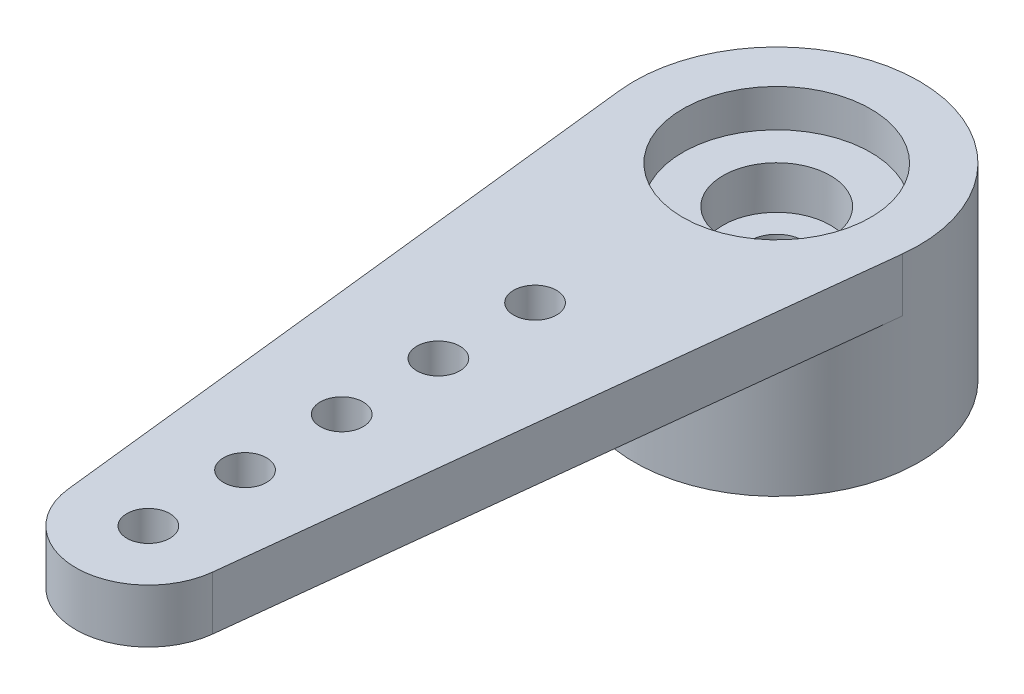
SolidWorks part; units mm, degrees
ref_plane "Front Plane" through (0, 0, 0) normal (0, 0, 1) x (1, 0, 0)
ref_plane "Top Plane" through (0, 0, 0) normal (0, 1, 0) x (1, 0, 0)
ref_plane "Right Plane" through (0, 0, 0) normal (1, 0, 0) x (0, 0, -1)
sketch "Sketch1" plane through (0, 0, 0) normal (0, 1, 0) x (1, 0, 0)
  line L0 (0, 0) -> (0, -14.859) construction
  line L1 (-1.7039, -15.0495) -> (-3.3447, -0.3739)
  line L2 (1.7039, -15.0495) -> (3.3447, -0.3739)
  arc A0 (3.3447, -0.3739) -> (-3.3447, -0.3739) centre (0, 0) ccw
  arc A1 (-1.7039, -15.0495) -> (1.7039, -15.0495) centre (0, -14.859) ccw
  dimension "D1" = 6.731
  dimension "D2" = 3.429
  dimension "D3" = 19.939
extrude "Boss-Extrude1" add sketch "Sketch1" along normal blind 1.27
sketch "Sketch2" plane through (0, 0, 0) normal (0, -1, 0) x (1, 0, 0)
  circle A0 centre (0, 0) radius 3.3655
extrude "Boss-Extrude2" add sketch "Sketch2" along normal blind 3.175
sketch "Sketch3" plane through (0, -3.175, 0) normal (0, -1, 0) x (-1, 0, 0)
  line L0 (0.3447, 2.4524) -> (0.1605, 2.2167)
  line L1 (0, 2.4765) -> (-0.1496, 2.2175)
  line L2 (0.4567, 2.1751) -> (0.3447, 2.4524)
  line L3 (0.1496, 2.2175) -> (0, 2.4765)
  line L4 (0.6826, 2.3806) -> (0.4675, 2.1728)
  line L5 (0.755, 2.0903) -> (0.6826, 2.3806)
  line L6 (1.0073, 2.2624) -> (0.7653, 2.0866)
  line L7 (1.0385, 1.9649) -> (1.0073, 2.2624)
  line L8 (1.3123, 2.1002) -> (1.0482, 1.9598)
  line L9 (1.3019, 1.8013) -> (1.3123, 2.1002)
  line L10 (1.5919, 1.8971) -> (1.3108, 1.7948)
  line L11 (1.5399, 1.6025) -> (1.5919, 1.8971)
  line L12 (1.8404, 1.6571) -> (1.5478, 1.5949)
  line L13 (1.748, 1.3726) -> (1.8404, 1.6571)
  line L14 (2.0531, 1.3848) -> (1.7547, 1.364)
  line L15 (1.922, 1.116) -> (2.0531, 1.3848)
  line L16 (2.2259, 1.0856) -> (1.9275, 1.1065)
  line L17 (2.0586, 0.8377) -> (2.2259, 1.0856)
  line L18 (2.3553, 0.7653) -> (2.0627, 0.8275)
  line L19 (2.1551, 0.543) -> (2.3553, 0.7653)
  line L20 (2.4389, 0.43) -> (2.1578, 0.5323)
  line L21 (2.2097, 0.2378) -> (2.4389, 0.43)
  line L22 (2.475, 0.0864) -> (2.2109, 0.2269)
  line L23 (2.2213, -0.0721) -> (2.475, 0.0864)
  line L24 (2.4629, -0.2589) -> (2.2209, -0.0831)
  line L25 (2.1897, -0.3805) -> (2.4629, -0.2589)
  line L26 (2.4029, -0.5991) -> (2.1878, -0.3913)
  line L27 (2.1154, -0.6816) -> (2.4029, -0.5991)
  line L28 (2.2962, -0.9277) -> (2.112, -0.692)
  line L29 (2, -0.9693) -> (2.2962, -0.9277)
  line L30 (2.1447, -1.2383) -> (1.9952, -0.9792)
  line L31 (1.8456, -1.2382) -> (2.1447, -1.2383)
  line L32 (1.9515, -1.5247) -> (1.8395, -1.2474)
  line L33 (1.6553, -1.4831) -> (1.9515, -1.5247)
  line L34 (1.7203, -1.7814) -> (1.648, -1.4912)
  line L35 (1.4328, -1.699) -> (1.7203, -1.7814)
  line L36 (1.4557, -2.0035) -> (1.4244, -1.7061)
  line L37 (1.1824, -1.8819) -> (1.4557, -2.0035)
  line L38 (1.1626, -2.1866) -> (1.1731, -1.8877)
  line L39 (0.909, -2.0281) -> (1.1626, -2.1866)
  line L40 (0.847, -2.3271) -> (0.899, -2.0326)
  line L41 (0.6179, -2.1349) -> (0.847, -2.3271)
  line L42 (0.5149, -2.4224) -> (0.6073, -2.1379)
  line L43 (0.3147, -2.2001) -> (0.5149, -2.4224)
  line L44 (0.1728, -2.4705) -> (0.3039, -2.2016)
  line L45 (-0.22, 2.0955) -> (0, 2.0955) [skipped]
  line L46 (0.0055, -2.2225) -> (0.1728, -2.4705)
  line L47 (-0.1728, -2.4705) -> (-0.0055, -2.2225)
  line L48 (-0.3039, -2.2016) -> (-0.1728, -2.4705)
  line L49 (-0.5149, -2.4224) -> (-0.3147, -2.2001)
  line L50 (-0.6073, -2.1379) -> (-0.5149, -2.4224)
  line L51 (-0.847, -2.3271) -> (-0.6179, -2.1349)
  line L52 (-0.899, -2.0326) -> (-0.847, -2.3271)
  line L53 (-1.1626, -2.1866) -> (-0.909, -2.0281)
  line L54 (-1.1731, -1.8877) -> (-1.1626, -2.1866)
  line L55 (-1.4557, -2.0035) -> (-1.1824, -1.8819)
  line L56 (-1.4244, -1.7061) -> (-1.4557, -2.0035)
  line L57 (-1.7203, -1.7814) -> (-1.4328, -1.699)
  line L58 (-1.648, -1.4912) -> (-1.7203, -1.7814)
  line L59 (-1.9515, -1.5247) -> (-1.6553, -1.4831)
  line L60 (-1.8395, -1.2474) -> (-1.9515, -1.5247)
  line L61 (-2.1447, -1.2382) -> (-1.8456, -1.2383)
  line L62 (-1.9952, -0.9792) -> (-2.1447, -1.2382)
  line L63 (-2.2962, -0.9277) -> (-2, -0.9693)
  line L64 (-2.112, -0.692) -> (-2.2962, -0.9277)
  line L65 (-2.4029, -0.5991) -> (-2.1154, -0.6816)
  line L66 (-2.1878, -0.3913) -> (-2.4029, -0.5991)
  line L67 (-2.4629, -0.2589) -> (-2.1897, -0.3805)
  line L68 (-2.2209, -0.0831) -> (-2.4629, -0.2589)
  line L69 (-2.475, 0.0864) -> (-2.2213, -0.0721)
  line L70 (-2.2109, 0.2269) -> (-2.475, 0.0864)
  line L71 (-2.4389, 0.43) -> (-2.2097, 0.2378)
  line L72 (-2.1578, 0.5323) -> (-2.4389, 0.43)
  line L73 (-2.3553, 0.7653) -> (-2.1551, 0.543)
  line L74 (-2.0627, 0.8275) -> (-2.3553, 0.7653)
  line L75 (-2.2259, 1.0856) -> (-2.0586, 0.8377)
  line L76 (-1.9275, 1.1065) -> (-2.2259, 1.0856)
  line L77 (-2.0531, 1.3848) -> (-1.922, 1.116)
  line L78 (-1.7547, 1.364) -> (-2.0531, 1.3848)
  line L79 (-1.8404, 1.6571) -> (-1.748, 1.3726)
  line L80 (-1.5478, 1.5949) -> (-1.8404, 1.6571)
  line L81 (-1.5919, 1.8971) -> (-1.5399, 1.6025)
  line L82 (-1.3108, 1.7948) -> (-1.5919, 1.8971)
  line L83 (-1.3123, 2.1002) -> (-1.3019, 1.8013)
  line L84 (-1.0482, 1.9598) -> (-1.3123, 2.1002)
  line L85 (-1.0073, 2.2624) -> (-1.0385, 1.9649)
  line L86 (-0.7653, 2.0866) -> (-1.0073, 2.2624)
  line L87 (-0.6826, 2.3806) -> (-0.755, 2.0903)
  line L88 (-0.4675, 2.1728) -> (-0.6826, 2.3806)
  line L89 (-0.3447, 2.4524) -> (-0.4567, 2.1751)
  line L90 (-0.1605, 2.2167) -> (-0.3447, 2.4524)
  arc A0 (-0.1496, 2.2175) -> (-0.1605, 2.2167) centre (0, 0) ccw
  circle A1 centre (0, 2.2225) radius 0.127 construction
  arc A2 (0.1605, 2.2167) -> (0.1496, 2.2175) centre (0, 0) ccw
  arc A3 (0.4675, 2.1728) -> (0.4567, 2.1751) centre (0, 0) ccw
  arc A4 (0.7653, 2.0866) -> (0.755, 2.0903) centre (0, 0) ccw
  arc A5 (1.0482, 1.9598) -> (1.0385, 1.9649) centre (0, 0) ccw
  arc A6 (1.3108, 1.7948) -> (1.3019, 1.8013) centre (0, 0) ccw
  arc A7 (1.5478, 1.5949) -> (1.5399, 1.6025) centre (0, 0) ccw
  arc A8 (1.7547, 1.364) -> (1.748, 1.3726) centre (0, 0) ccw
  arc A9 (1.9275, 1.1065) -> (1.922, 1.116) centre (0, 0) ccw
  arc A10 (-0.4567, 2.1751) -> (-0.4675, 2.1728) centre (0, 0) ccw
  arc A11 (-0.755, 2.0903) -> (-0.7653, 2.0866) centre (0, 0) ccw
  arc A12 (-1.0385, 1.9649) -> (-1.0482, 1.9598) centre (0, 0) ccw
  arc A13 (-1.3019, 1.8013) -> (-1.3108, 1.7948) centre (0, 0) ccw
  arc A14 (-1.5399, 1.6025) -> (-1.5478, 1.5949) centre (0, 0) ccw
  arc A15 (-1.748, 1.3726) -> (-1.7547, 1.364) centre (0, 0) ccw
  arc A16 (-1.922, 1.116) -> (-1.9275, 1.1065) centre (0, 0) ccw
  arc A17 (-2.0586, 0.8377) -> (-2.0627, 0.8275) centre (0, 0) ccw
  arc A18 (-2.1551, 0.543) -> (-2.1578, 0.5323) centre (0, 0) ccw
  arc A19 (-2.2097, 0.2378) -> (-2.2109, 0.2269) centre (0, 0) ccw
  arc A20 (-2.2213, -0.0721) -> (-2.2209, -0.0831) centre (0, 0) ccw
  arc A21 (2.0627, 0.8275) -> (2.0586, 0.8377) centre (0, 0) ccw
  arc A22 (2.1578, 0.5323) -> (2.1551, 0.543) centre (0, 0) ccw
  arc A23 (2.2109, 0.2269) -> (2.2097, 0.2378) centre (0, 0) ccw
  arc A24 (2.2209, -0.0831) -> (2.2213, -0.0721) centre (0, 0) ccw
  arc A25 (2.1878, -0.3913) -> (2.1897, -0.3805) centre (0, 0) ccw
  arc A26 (2.112, -0.692) -> (2.1154, -0.6816) centre (0, 0) ccw
  arc A27 (1.9952, -0.9792) -> (2, -0.9693) centre (0, 0) ccw
  arc A28 (1.8395, -1.2474) -> (1.8456, -1.2382) centre (0, 0) ccw
  arc A29 (1.648, -1.4912) -> (1.6553, -1.4831) centre (0, 0) ccw
  arc A30 (1.4244, -1.7061) -> (1.4328, -1.699) centre (0, 0) ccw
  arc A31 (1.1731, -1.8877) -> (1.1824, -1.8819) centre (0, 0) ccw
  arc A32 (0.899, -2.0326) -> (0.909, -2.0281) centre (0, 0) ccw
  arc A33 (0.6073, -2.1379) -> (0.6179, -2.1349) centre (0, 0) ccw
  arc A34 (0.3039, -2.2016) -> (0.3147, -2.2001) centre (0, 0) ccw
  arc A35 (-0.0055, -2.2225) -> (0.0055, -2.2225) centre (0, 0) ccw
  arc A36 (-0.3147, -2.2001) -> (-0.3039, -2.2016) centre (0, 0) ccw
  arc A37 (-0.6179, -2.1349) -> (-0.6073, -2.1379) centre (0, 0) ccw
  arc A38 (-0.909, -2.0281) -> (-0.899, -2.0326) centre (0, 0) ccw
  arc A39 (-1.1824, -1.8819) -> (-1.1731, -1.8877) centre (0, 0) ccw
  arc A40 (-1.4328, -1.699) -> (-1.4244, -1.7061) centre (0, 0) ccw
  arc A41 (-1.6553, -1.4831) -> (-1.648, -1.4912) centre (0, 0) ccw
  arc A42 (-1.8456, -1.2383) -> (-1.8395, -1.2474) centre (0, 0) ccw
  arc A43 (-2, -0.9693) -> (-1.9952, -0.9792) centre (0, 0) ccw
  arc A44 (-2.1154, -0.6816) -> (-2.112, -0.692) centre (0, 0) ccw
  arc A45 (-2.1897, -0.3805) -> (-2.1878, -0.3913) centre (0, 0) ccw
  point P145 (0, 0)
  dimension "D1" = 4.445
  dimension "D2" = 0.254
  dimension "D3" = 45
extrude "Cut-Extrude1" cut sketch "Sketch3" against normal blind 2.286
sketch "Sketch4" plane through (0, 1.27, 0) normal (0, 1, 0) x (1, 0, 0)
  circle A0 centre (0, 0) radius 2.2225
  dimension "D1" = 4.445
extrude "Cut-Extrude2" cut sketch "Sketch4" against normal blind 0.889
sketch "Sketch5" plane through (0, 0.381, 0) normal (0, 1, 0) x (1, 0, 0)
  circle A0 centre (0, 0) radius 1.27
  dimension "D1" = 2.54
extrude "Cut-Extrude3" cut sketch "Sketch5" against normal up to next
sketch "Sketch6" plane through (0, 1.27, 0) normal (0, 1, 0) x (1, 0, 0)
  line L0 (0, 0) -> (0, -14.859) construction
  circle A0 centre (0, -14.859) radius 0.508
  circle A1 centre (0, -12.573) radius 0.508
  circle A2 centre (0, -10.287) radius 0.508
  circle A3 centre (0, -8.001) radius 0.508
  circle A4 centre (0, -5.715) radius 0.508
  dimension "D1" = 1.016
  dimension "D2" = 1.016
  dimension "D3" = 1.27
  dimension "D4" = 1.27
  dimension "D5" = 1.27
  dimension "D6" = 1.27
extrude "Cut-Extrude4" cut sketch "Sketch6" against normal up to next
sketch "Sketch7" plane through (0, -3.175, 0) normal (0, -1, 0) x (1, 0, 0)
  circle A0 centre (0, 0) radius 0.635
  circle A1 centre (0, 0) radius 2.54
  dimension "D1" = 1.27
extrude "Boss-Extrude3" add sketch "Sketch7" against normal blind 2.54
